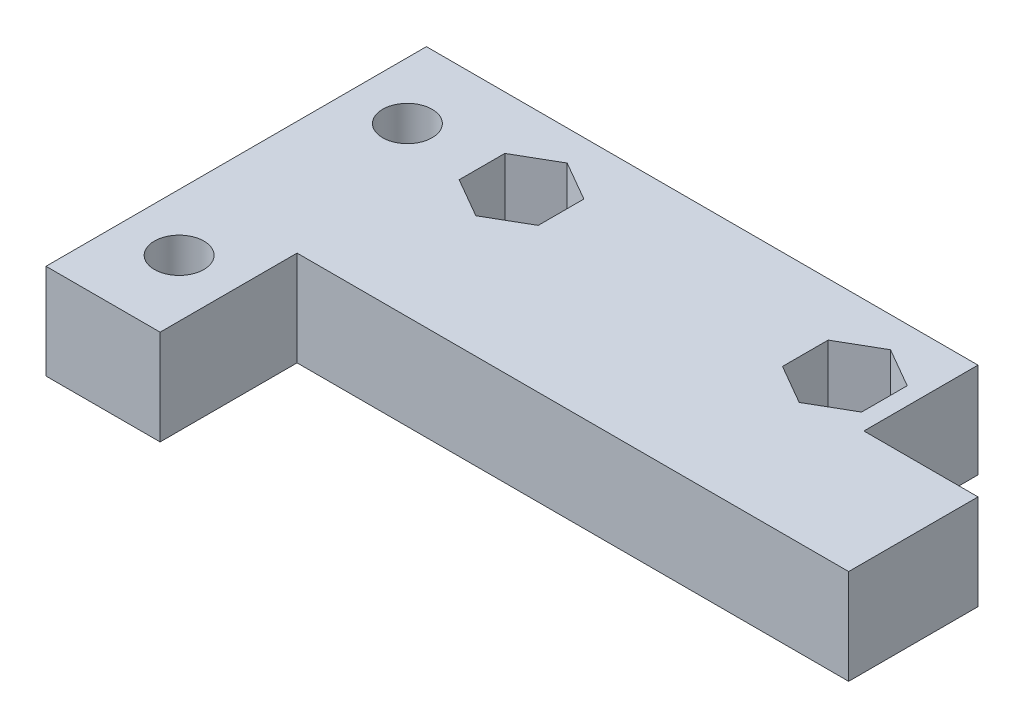
SolidWorks part; units mm, degrees
ref_plane "前基準面" through (0, 0, 0) normal (0, 0, 1) x (1, 0, 0)
ref_plane "上基準面" through (0, 0, 0) normal (0, 1, 0) x (1, 0, 0)
ref_plane "右基準面" through (0, 0, 0) normal (1, 0, 0) x (0, 0, -1)
sketch "草圖1" plane through (0, 0, 0) normal (0, 1, 0) x (1, 0, 0)
  line L1 (0, 0) -> (35, 0)
  line L2 (0, 0) -> (0, 20)
  line L3 (0, 20) -> (35, 20)
  line L4 (35, 0) -> (35, 20)
  dimension "D1" = 35
  dimension "D2" = 20
extrude "填料-伸長1" add sketch "草圖1" along normal blind 8
sketch "草圖2" plane through (0, 0, 0) normal (0, 1, 0) x (1, 0, 0)
  line L0 (0, 20) -> (0, 0) construction
  line L1 (6, 0) -> (35, 0)
  line L2 (6, 0) -> (6, 14)
  line L3 (6, 14) -> (35, 14)
  line L4 (35, 0) -> (35, 14)
  dimension "D1" = 29
  dimension "D2" = 14
  dimension "D3" = 6
  dimension "D4" = 14
extrude "除料-伸長2" cut sketch "草圖2" along normal blind 0.8
sketch "草圖3" plane through (0, 0, 0) normal (0, 1, 0) x (1, 0, 0)
  line L1 (6, 0) -> (35, 0)
  line L2 (6, 0) -> (6, 7.2)
  line L3 (6, 7.2) -> (35, 7.2)
  line L4 (35, 0) -> (35, 7.2)
  dimension "D1" = 29
  dimension "D2" = 7.2
extrude "除料-伸長4" cut sketch "草圖3" along normal through all
sketch "草圖4" plane through (0, 0, 0) normal (0, 1, 0) x (1, 0, 0)
  line L1 (35, 20) -> (29, 20)
  line L2 (35, 20) -> (35, 14)
  line L3 (35, 14) -> (29, 14)
  line L4 (29, 20) -> (29, 14)
  dimension "D1" = 6
  dimension "D2" = 6
extrude "除料-伸長5" cut sketch "草圖4" along normal through all
sketch "草圖5" plane through (0, 0, 0) normal (0, 1, 0) x (1, 0, 0)
  circle A0 centre (3, 16) radius 1.3
  circle A1 centre (3, 4) radius 1.3
  circle A2 centre (9, 16) radius 1.3
  circle A4 centre (26, 16) radius 1.3
extrude "除料-伸長6" cut sketch "草圖5" along normal through all
sketch "草圖7" plane through (0, 0, 0) normal (0, 1, 0) x (1, 0, 0)
  line L1 (26, 18.4) -> (23.9215, 17.2)
  line L2 (23.9215, 17.2) -> (23.9215, 14.8)
  line L3 (23.9215, 14.8) -> (26, 13.6)
  line L4 (26, 13.6) -> (28.0785, 14.8)
  line L5 (28.0785, 14.8) -> (28.0785, 17.2)
  line L6 (28.0785, 17.2) -> (26, 18.4)
  line L8 (9, 18.4) -> (6.9215, 17.2)
  line L9 (6.9215, 17.2) -> (6.9215, 14.8)
  line L10 (6.9215, 14.8) -> (9, 13.6)
  line L11 (9, 13.6) -> (11.0785, 14.8)
  line L12 (11.0785, 14.8) -> (11.0785, 17.2)
  line L13 (11.0785, 17.2) -> (9, 18.4)
  circle A0 centre (9, 16) radius 2.0785 construction
  circle A1 centre (26, 16) radius 2.0785 construction
  dimension "D1" = 4.8
  dimension "D2" = 4.8
extrude "除料-伸長8" cut sketch "草圖7" against normal through all from surface at 8 starting at face at (9, 8, -14.7)
sketch "草圖6" plane through (0, 0, 0) normal (0, 1, 0) x (1, 0, 0)
  circle A1 centre (3, 16) radius 2.2
  circle A2 centre (3, 4) radius 2.2
extrude "除料-伸長10" cut sketch "草圖6" along normal blind 2 from surface at 0 starting at face at (15.75, 0, -14.44)
sketch "草圖8" plane through (0, 0, 0) normal (0, 1, 0) x (1, 0, 0)
  line L0 (35, 7.2) -> (35, 14) construction
  line L1 (0, 0) -> (35, 0)
  line L2 (0, 0) -> (0, 20)
  line L3 (0, 20) -> (35, 20)
  line L4 (35, 0) -> (35, 20)
  line L5 (0, 0) -> (6, 0) construction
  dimension "D1" = 0
  dimension "D2" = 20
extrude "除料-伸長11" cut sketch "草圖8" along normal blind 3
